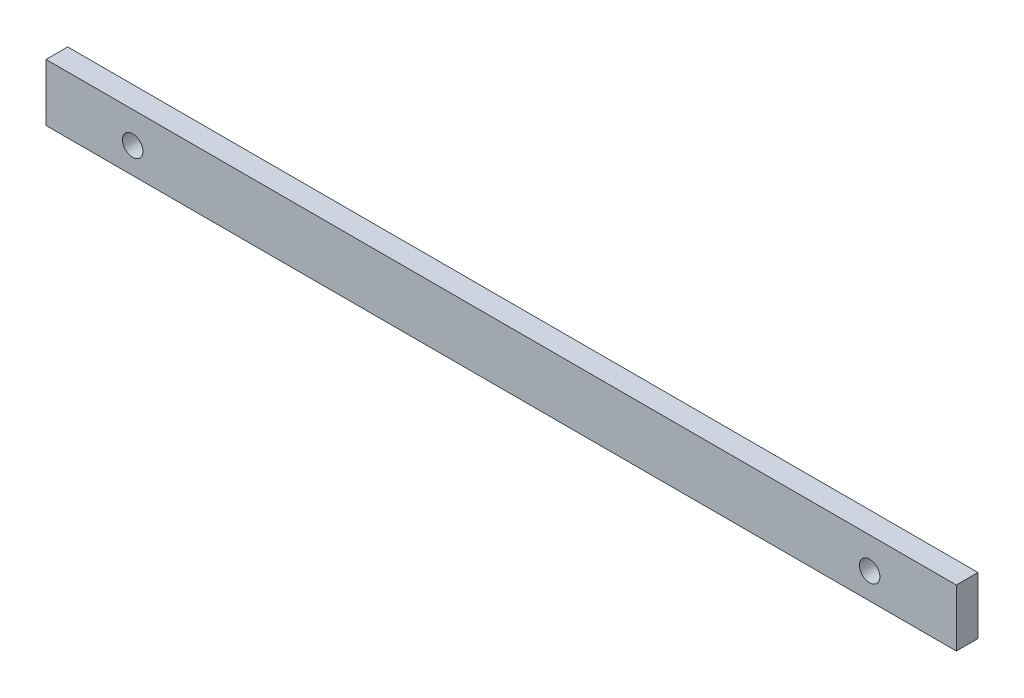
SolidWorks part; units mm, degrees
ref_plane "Front Plane" through (0, 0, 0) normal (0, 0, 1) x (1, 0, 0)
ref_plane "Top Plane" through (0, 0, 0) normal (0, 1, 0) x (1, 0, 0)
ref_plane "Right Plane" through (0, 0, 0) normal (1, 0, 0) x (0, 0, -1)
sketch "Sketch3" plane through (0, 0, 0) normal (0, 0, 1) x (1, 0, 0)
  line L0 (-53.975, -0.381) -> (53.975, -0.381) construction
  line L1 (63.5, 4.191) -> (-63.5, 4.191)
  line L2 (63.5, 4.191) -> (63.5, -4.191)
  line L3 (63.5, -4.191) -> (-63.5, -4.191)
  line L4 (-63.5, 4.191) -> (-63.5, -4.191)
  line L5 (63.5, 4.191) -> (-63.5, -4.191) construction
  line L6 (63.5, -4.191) -> (-63.5, 4.191) construction
  line L7 (-63.5, 4.191) -> (-66.675, 4.191)
  line L8 (-63.5, 4.191) -> (-63.5, -4.191)
  line L9 (-63.5, -4.191) -> (-66.675, -4.191)
  line L10 (-66.675, 4.191) -> (-66.675, -4.191)
  line L11 (63.5, 4.191) -> (66.675, 4.191)
  line L12 (63.5, 4.191) -> (63.5, -4.191)
  line L13 (63.5, -4.191) -> (66.675, -4.191)
  line L14 (66.675, 4.191) -> (66.675, -4.191)
  circle A0 centre (-53.975, -0.381) radius 1.5
  circle A1 centre (53.975, -0.381) radius 1.5
  point P0 (0, 0)
  point P14 (0, -0.381)
  dimension "D4" = 3
  dimension "D1" = 127
  dimension "D2" = 8.382
  dimension "D3" = 3.175
  dimension "D5" = 3.81
  dimension "D6" = 9.525
extrude "Boss-Extrude1" add sketch "Sketch3" along normal blind 3.175 contours L7 L10 L9 L4 | L1 L4 L3 L2 A1 A0 | L14 L11 L2 L13
